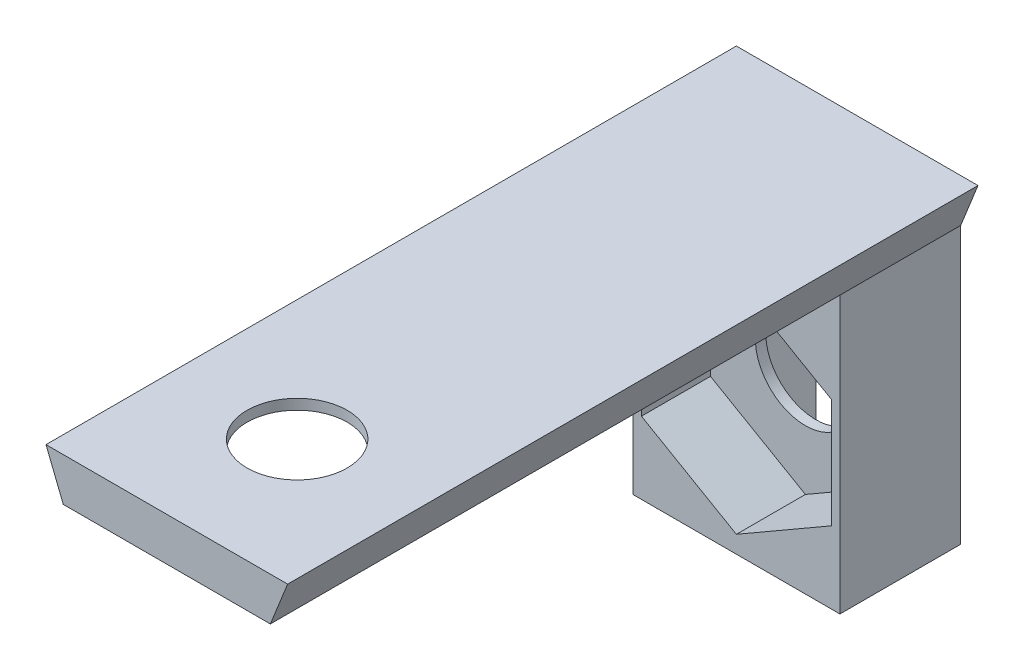
SolidWorks part; units mm, degrees
ref_plane "Front Plane" through (0, 0, 0) normal (0, 0, 1) x (1, 0, 0)
ref_plane "Top Plane" through (0, 0, 0) normal (0, 1, 0) x (1, 0, 0)
ref_plane "Right Plane" through (0, 0, 0) normal (1, 0, 0) x (0, 0, -1)
sketch "Sketch1" plane through (0, 0, 0) normal (0, 1, 0) x (1, 0, 0)
  line L1 (-6, -3.5) -> (6, -3.5)
  line L2 (-6, -3.5) -> (-6, 3.5)
  line L3 (-6, 3.5) -> (6, 3.5)
  line L4 (6, -3.5) -> (6, 3.5)
  line L5 (-6, -3.5) -> (6, 3.5) construction
  line L6 (-6, 3.5) -> (6, -3.5) construction
  point P0 (0, 0)
extrude "Boss-Extrude1" add sketch "Sketch1" along normal blind 16
sketch "Sketch2" plane through (0, 16, 0) normal (0, 1, 0) x (1, 0, 0)
  line L0 (0, 3.5) -> (0, 1.1) construction
  line L1 (6, 3.5) -> (-6, 3.5) construction
  line L22 (0, 3.5) -> (2.4, 3.5)
  line L23 (0, 3.5) -> (-2.4, 3.5)
  line L24 (2.4, 3.5) -> (4.8, 1.1)
  line L25 (0, 1.1) -> (4.8, 1.1)
  line L26 (-2.4, 3.5) -> (-4.8, 1.1)
  line L27 (0, 1.1) -> (-4.8, 1.1)
extrude "Cut-Extrude1" cut sketch "Sketch2" against normal blind 20
sketch "Sketch3" plane through (0, 0, 3.5) normal (0, 0, 1) x (1, 0, 0)
  line L0 (0, 0) -> (0, 7.35) construction
  circle A0 centre (0, 7.35) radius 2.9
extrude "Cut-Extrude2" cut sketch "Sketch3" against normal up to next
sketch "Sketch4" plane through (0, 0, 3.5) normal (0, 0, 1) x (1, 0, 0)
  line L0 (0, 0) -> (0, 7.35) construction
  line L1 (0, 13.7009) -> (-5.5, 10.5254)
  line L2 (-5.5, 10.5254) -> (-5.5, 4.1746)
  line L3 (-5.5, 4.1746) -> (0, 0.9991)
  line L4 (0, 0.9991) -> (5.5, 4.1746)
  line L5 (5.5, 4.1746) -> (5.5, 10.5254)
  line L6 (5.5, 10.5254) -> (0, 13.7009)
  circle A0 centre (0, 7.35) radius 5.5 construction
extrude "Cut-Extrude3" cut sketch "Sketch4" against normal blind 4
sketch "Sketch5" plane through (0, 16, 0) normal (0, 1, 0) x (1, 0, 0)
  line L0 (-6, 3.5) -> (-7, 3.5) construction
  line L1 (6, 3.5) -> (7, 3.5) construction
  line L3 (-7, 3.5) -> (7, 3.5)
  line L4 (-7, 3.5) -> (-7, -36.5)
  line L5 (-7, -36.5) -> (7, -36.5)
  line L6 (7, 3.5) -> (7, -36.5)
extrude "Boss-Extrude2" add sketch "Sketch5" along normal blind 2.5
sketch "Sketch6" plane through (0, 0, -3.5) normal (0, 0, -1) x (-1, 0, 0)
  line L0 (-7, 16) -> (-7, 18.5)
  line L1 (-7, 18.5) -> (-6, 16)
  line L2 (-6, 16) -> (-7, 16)
  line L3 (7, 16) -> (6, 16)
  line L4 (6, 16) -> (7, 18.5)
  line L5 (7, 18.5) -> (7, 16)
extrude "Cut-Extrude4" cut sketch "Sketch6" against normal up to next
sketch "Sketch8" plane through (0, 16, 0) normal (0, -1, 0) x (1, 0, 0)
  line L1 (0, 22.5991) -> (5.5, 25.7746)
  line L2 (5.5, 25.7746) -> (5.5, 32.1254)
  line L3 (5.5, 32.1254) -> (0, 35.3009)
  line L4 (0, 35.3009) -> (-5.5, 32.1254)
  line L5 (-5.5, 32.1254) -> (-5.5, 25.7746)
  line L6 (-5.5, 25.7746) -> (0, 22.5991)
  line L7 (0, 36.5) -> (0, 28.95) construction
  line L8 (-6, 36.5) -> (6, 36.5) construction
  circle A0 centre (0, 28.95) radius 5.5 construction
extrude "Cut-Extrude6" cut sketch "Sketch8" against normal blind 1.9
sketch "Sketch9" plane through (0, 17.9, 0) normal (0, -1, 0) x (-1, 0, 0)
  circle A0 centre (0, -28.95) radius 2.9
extrude "Cut-Extrude7" cut sketch "Sketch9" against normal up to next
